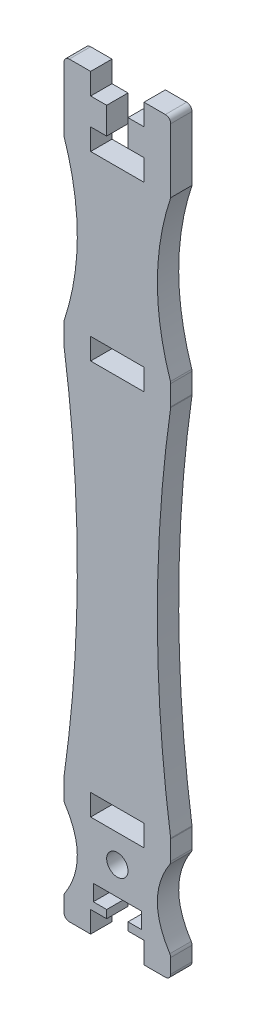
SolidWorks part; units mm, degrees
ref_plane "Alzado" through (0, 0, 0) normal (0, 0, 1) x (1, 0, 0)
ref_plane "Planta" through (0, 0, 0) normal (0, 1, 0) x (1, 0, 0)
ref_plane "Vista lateral" through (0, 0, 0) normal (1, 0, 0) x (0, 0, -1)
sketch "Croquis1" plane through (0, 0, 0) normal (0, 0, 1) x (1, 0, 0)
  line L0 (-10, -70) -> (-14, -70)
  line L1 (-10, 70) -> (-10, 66)
  line L2 (-15, 69) -> (-15, 61)
  line L3 (0, -70) -> (4, -70)
  line L4 (5, 69) -> (5, 61)
  line L5 (0, -66) -> (-3, -66)
  line L6 (0, -66) -> (0, -70)
  line L7 (-0.5, -61.5) -> (-9.5, -61.5)
  line L8 (-10, -66) -> (-10, -70)
  line L10 (-10, -66) -> (-10, -51)
  line L11 (-10, -51) -> (0, -51)
  line L12 (0, -51) -> (0, -66)
  line L13 (-0.5, -61.5) -> (-0.5, -64.5)
  line L14 (-0.5, -64.5) -> (-3, -64.5)
  line L15 (0, -51) -> (0, -47)
  line L16 (0, -47) -> (-10, -47)
  line L17 (-10, -47) -> (-10, -51)
  line L18 (-3, -64.5) -> (-3, -66)
  line L19 (-7, -64.5) -> (-7, -66)
  line L20 (0, -47) -> (0, 23)
  line L21 (-10, -47) -> (-10, 23)
  line L22 (-10, 23) -> (0, 23)
  line L23 (0, 23) -> (0, 27)
  line L24 (0, 27) -> (-10, 27)
  line L25 (-10, 27) -> (-10, 23)
  line L26 (-9.5, -64.5) -> (-7, -64.5)
  line L27 (-9.5, -61.5) -> (-9.5, -64.5)
  line L28 (-10, -66) -> (-7, -66)
  line L29 (-15, -69) -> (-15, -66.2986)
  line L30 (0, 27) -> (0, 57)
  line L31 (0, 57) -> (-10, 57)
  line L32 (-10, 57) -> (-10, 27)
  line L33 (0, 57) -> (0, 61)
  line L34 (-3, 61) -> (0, 61)
  line L35 (-10, 61) -> (-10, 57)
  line L36 (-10, 70) -> (-14, 70)
  line L37 (-7, 61) -> (-10, 61)
  line L38 (0, 70) -> (4, 70)
  line L39 (0, 66) -> (0, 70)
  line L41 (-10, 61) -> (-15, 61)
  line L42 (0, 61) -> (5, 61)
  line L43 (5, -66.2986) -> (5, -69)
  line L44 (0, 61) -> (0, 66)
  line L45 (-10, 61) -> (-10, 66)
  line L46 (-10, 66) -> (-15, 66)
  line L47 (0, 66) -> (5, 66)
  line L48 (-15, 61) -> (-15, 57)
  line L55 (5, -47.071) -> (5, -50.7014)
  line L57 (-15, -47.071) -> (-15, -50.7014)
  line L58 (5, 61) -> (5, 57)
  line L65 (5, 23.071) -> (5, 26.8385)
  line L67 (-15, 23.071) -> (-15, 26.8385)
  line L73 (-3, 66) -> (-3, 61)
  line L74 (-3, 66) -> (0, 66)
  line L75 (-7, 66) -> (-7, 61)
  line L76 (-7, 66) -> (-10, 66)
  arc A0 (4, 70) -> (5, 69) centre (4, 69) cw
  arc A1 (-15, 69) -> (-14, 70) centre (-14, 69) cw
  arc A2 (4, -70) -> (5, -69) centre (4, -69) ccw
  arc A3 (-14, -70) -> (-15, -69) centre (-14, -69) cw
  arc A4 (-14.8403, -65.7566) -> (-15, -66.2986) centre (-14, -66.2986) ccw
  arc A5 (4.8403, -65.7566) -> (5, -66.2986) centre (4, -66.2986) cw
  arc A6 (4.99, -46.9299) -> (5, -47.071) centre (4, -47.071) cw
  arc A7 (4.8403, -51.2434) -> (5, -50.7014) centre (4, -50.7014) ccw
  arc A8 (-15, -50.7014) -> (-14.8403, -51.2434) centre (-14, -50.7014) ccw
  arc A9 (-14.99, -46.9299) -> (-15, -47.071) centre (-14, -47.071) ccw
  arc A10 (4.99, 22.9299) -> (5, 23.071) centre (4, 23.071) ccw
  arc A11 (4.9496, 27.1518) -> (5, 26.8385) centre (4, 26.8385) cw
  arc A12 (-15, 26.8385) -> (-14.9496, 27.1518) centre (-14, 26.8385) cw
  arc A13 (-14.99, 22.9299) -> (-15, 23.071) centre (-14, 23.071) cw
  circle A16 centre (-5, -56.25) radius 2
  spline S0 degree 3 poles (-14.8403, -51.2434) (-13.2801, -53.6623) (-11.7199, -58.5) (-13.2801, -63.3377) (-14.8403, -65.7566) knots 0.016229 0.016229 0.016229 0.016229 0.5 0.983771 0.983771 0.983771 0.983771
  spline S1 degree 3 poles (4.8403, -65.7566) (3.2801, -63.3377) (1.7199, -58.5) (3.2801, -53.6623) (4.8403, -51.2434) knots 0.016229 0.016229 0.016229 0.016229 0.5 0.983771 0.983771 0.983771 0.983771
  spline S2 degree 3 poles (-14.9496, 27.1518) (-11.6668, 37.1012) (-11.6835, 47.0561) (-15, 57) knots 0.005062 0.005062 0.005062 0.005062 1 1 1 1
  spline S3 degree 3 poles (4.9496, 27.1518) (1.6668, 37.1012) (1.6835, 47.0561) (5, 57) knots 0.005062 0.005062 0.005062 0.005062 1 1 1 1
  spline S4 degree 3 poles (-14.99, -46.9299) (-13.33, -35.2866) (-11.67, -12) (-13.33, 11.2866) (-14.99, 22.9299) knots 0.001002 0.001002 0.001002 0.001002 0.5 0.998998 0.998998 0.998998 0.998998
  spline S5 degree 3 poles (4.99, -46.9299) (3.33, -35.2866) (1.67, -12) (3.33, 11.2866) (4.99, 22.9299) knots 0.001002 0.001002 0.001002 0.001002 0.5 0.998998 0.998998 0.998998 0.998998
  point P7 (-15, 0)
  dimension "D1" = 1
  dimension "D2" = 1
extrude "Saliente-Extruir1" add sketch "Croquis1" along normal blind 4
